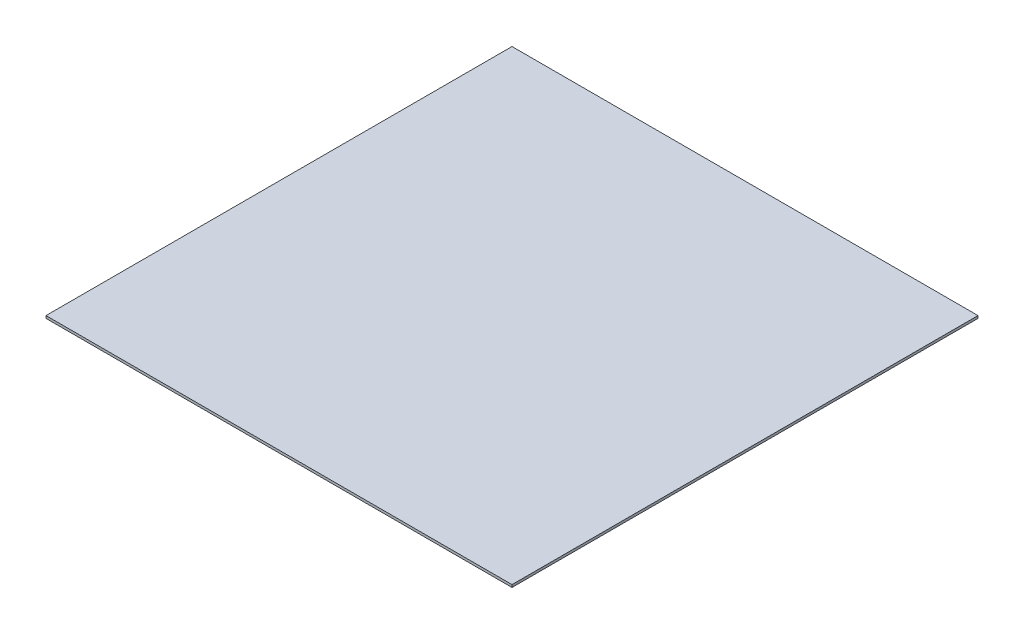
SolidWorks part; units mm, degrees
ref_plane "Front Plane" through (0, 0, 0) normal (0, 0, 1) x (1, 0, 0)
ref_plane "Top Plane" through (0, 0, 0) normal (0, 1, 0) x (1, 0, 0)
ref_plane "Right Plane" through (0, 0, 0) normal (1, 0, 0) x (0, 0, -1)
sketch "Sketch2" plane through (0, 0, 0) normal (0, 1, 0) x (1, 0, 0)
  line L1 (-150, -150) -> (150, -150)
  line L2 (-150, -150) -> (-150, 150)
  line L3 (-150, 150) -> (150, 150)
  line L4 (150, -150) -> (150, 150)
  line L5 (-150, -150) -> (150, 150) construction
  line L6 (-150, 150) -> (150, -150) construction
  point P0 (0, 0)
  dimension "D1" = 300
  dimension "D2" = 300
extrude "Boss-Extrude1" add sketch "Sketch2" along normal blind 1.6
